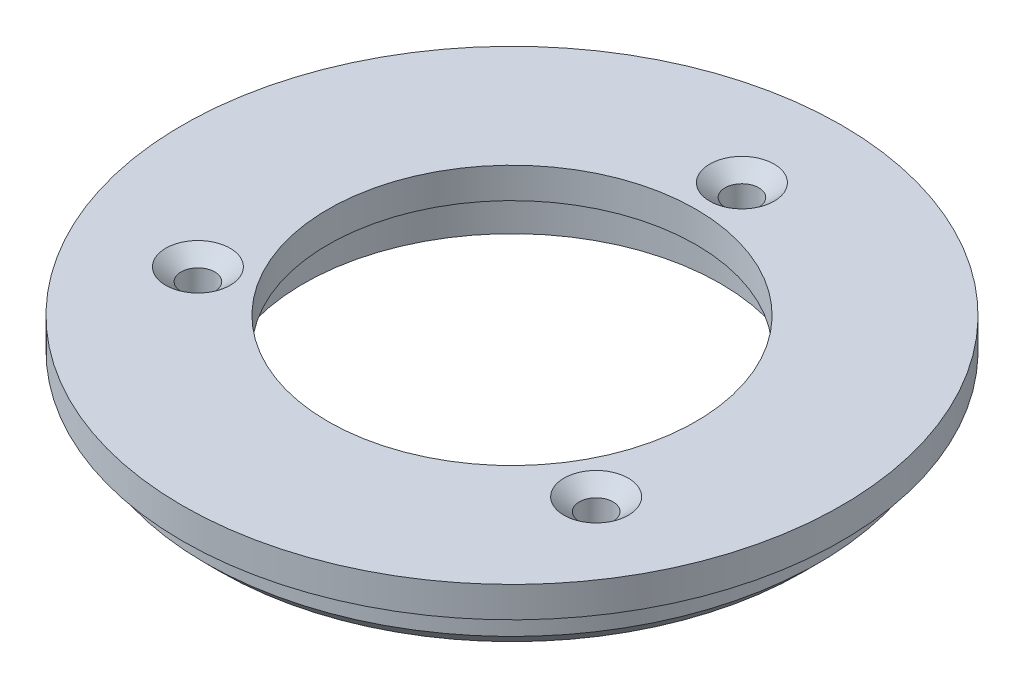
SolidWorks part; units mm, degrees
ref_plane "Front Plane" through (0, 0, 0) normal (0, 0, 1) x (1, 0, 0)
ref_plane "Top Plane" through (0, 0, 0) normal (0, 1, 0) x (1, 0, 0)
ref_plane "Right Plane" through (0, 0, 0) normal (1, 0, 0) x (0, 0, -1)
sketch "Sketch1" plane through (0, 0, 0) normal (0, 1, 0) x (1, 0, 0)
  circle A0 centre (0, 0) radius 21.5
  circle A1 centre (0, 0) radius 12
  dimension "D1" = 43
  dimension "D2" = 24
extrude "Boss-Extrude1" add sketch "Sketch1" against normal blind 2
sketch "Sketch2" plane through (0, -2, 0) normal (0, -1, 0) x (1, 0, 0)
  circle A0 centre (0, 0) radius 20
  circle A1 centre (0, 0) radius 13.6
  dimension "D1" = 40
  dimension "D2" = 27.2
extrude "Boss-Extrude2" add sketch "Sketch2" along normal blind 3
sketch "Sketch3" plane through (0, 0, 0) normal (0, 1, 0) x (1, 0, 0)
  line L0 (0, 0) -> (0, 28.1653) construction
  circle A0 centre (0, 15) radius 1.1
  circle A2 centre (12.9904, -7.5) radius 1.1
  circle A3 centre (-12.9904, -7.5) radius 1.1
  point P12 (0, 0)
  dimension "D1" = 2.2
  dimension "D2" = 15
  dimension "D3" = 3
chamfer "Chamfer1" distance 1 angle 45 1 edges at (0, -5, -20)
sketch "Sketch6" plane through (0, 0, 0) normal (0, 1, 0) x (1, 0, 0)
  point P0 (0, 15)
  point P3 (12.9904, -7.5)
  point P6 (-12.9904, -7.5)
hole_wizard "CSK for #0 Flat Head Machine Screw (100)1" positions "Sketch6" profile "Sketch5" countersink size "#0" standard "ANSI Inch" end condition through all
sketch "Sketch5" plane through (0, 0, -15) normal (1, 0, 0) x (0, 0, 1)
  line L0 (0, 0) -> (0, 5)
  line L1 (0, 5) -> (1.1, 5)
  line L2 (1.1, 5) -> (1.1, 0.8391)
  line L3 (1.1, 0.8391) -> (2.1, 0)
  line L5 (2.1, 0) -> (0, 0)
  line L6 (-1.1, 0.8391) -> (-2.1, 0) construction
  line L11 (0, -6.35) -> (0, 107.95) construction
  dimension "Thru Hole Dia." = 2.2
  dimension "Thru Hole Depth" = 5
  dimension "Near C'Sink Dia." = 4.2
  dimension "Near C'Sink Angle" = 100
